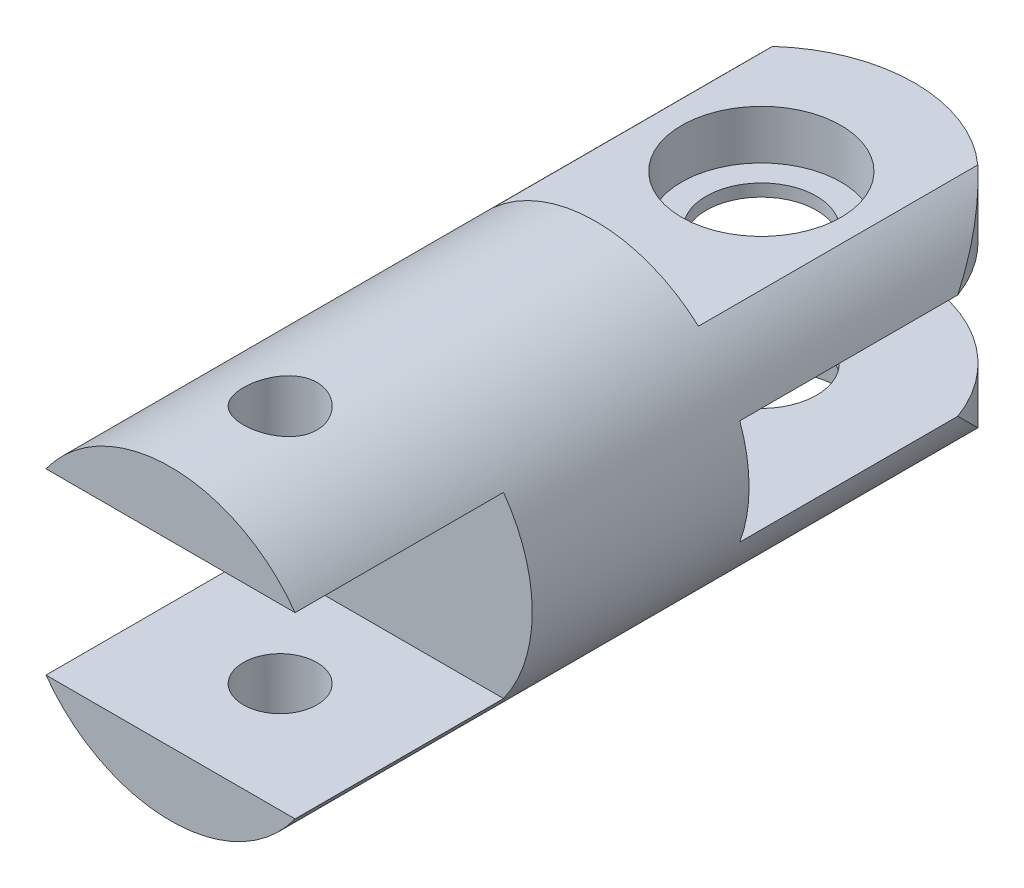
SolidWorks part; units mm, degrees
ref_plane "정면" through (0, 0, 0) normal (0, 0, 1) x (1, 0, 0)
ref_plane "윗면" through (0, 0, 0) normal (0, 1, 0) x (1, 0, 0)
ref_plane "우측면" through (0, 0, 0) normal (1, 0, 0) x (0, 0, -1)
sketch "스케치1" plane through (0, 0, 0) normal (0, 0, 1) x (1, 0, 0)
  circle A0 centre (0, 0) radius 12.5
  dimension "D1" = 25
extrude "보스-돌출1" add sketch "스케치1" against normal blind 60.6869 contours A0
sketch "스케치2" plane through (0, 0, -60.6869) normal (0, 0, -1) x (-1, 0, 0)
  line L0 (18.4039, 0) -> (-28.4221, 0) construction
  line L1 (8.3714, 9.2827) -> (-8.3714, 9.2827)
  line L2 (11.7434, 4.2827) -> (-11.7434, 4.2827)
  line L3 (8.3714, -9.2827) -> (-8.3714, -9.2827)
  line L4 (11.7434, -4.2827) -> (-11.7434, -4.2827)
  arc A0 (-11.7434, 4.2827) -> (-11.7434, -4.2827) centre (0, 0) ccw
  circle A1 centre (0, 0) radius 12.5
  arc A2 (8.3714, 9.2827) -> (-8.3714, 9.2827) centre (0, 0) ccw
  arc A3 (-8.3714, -9.2827) -> (8.3714, -9.2827) centre (0, 0) ccw
  arc A4 (11.7434, -4.2827) -> (11.7434, 4.2827) centre (0, 0) ccw
  point P8 (-11.8869, 3.8668)
  dimension "D3" = 5
  dimension "D1" = 0
extrude "컷-돌출1" cut sketch "스케치2" against normal blind 26
ref_plane "평면4" through (12.5, 0, 0) normal (1, 0, 0) x (0, 0, -1)
ref_plane "평면2" through (0, 0, -30.3435) normal (0, 0, -1) x (-1, 0, 0)
sketch "스케치3" plane through (0, 9.2827, 0) normal (0, 1, 0) x (1, 0, 0)
  line L1 (0, 17.9498) -> (0, -5.5116) construction
  line L2 (8.3714, 34.6869) -> (-8.3714, 34.6869) construction
  line L4 (12.5, 0) -> (12.5, 34.6869) construction
  line L5 (12.5, 0) -> (12.5, 64.839) construction
  line L6 (0, 48.1869) -> (50.0464, 48.1869) construction
  line L7 (-22.5, 48.1869) -> (-12.5, 48.1869)
  line L8 (12.5, 48.1869) -> (22.5, 48.1869)
  circle A0 centre (0, 48.1869) radius 4.5
  arc A1 (12.5, 48.1869) -> (-12.5, 48.1869) centre (0, 48.1869) ccw
  arc A2 (22.5, 48.1869) -> (-22.5, 48.1869) centre (0, 48.1869) ccw
  dimension "D1" = 9
  dimension "D2" = 13.5
  dimension "D3" = 10
extrude "컷-돌출2" cut sketch "스케치3" against normal blind 34.1239
sketch "스케치6" plane through (0, 9.2827, 0) normal (0, 1, 0) x (1, 0, 0)
  circle A0 centre (0, 48.1869) radius 6.5
  dimension "D1" = 13
extrude "컷-돌출5" cut sketch "스케치6" against normal blind 4
ref_plane "평면1" through (0, 0, 0) normal (0, -1, 0) x (-1, 0, 0)
mirror "대칭 복사3" about plane through (0, 0, 0) normal (0, 1, 0) of "컷-돌출5"
sketch "스케치8" plane through (0, 0, 0) normal (0, 0, 1) x (1, 0, 0)
  line L0 (10.1592, 7.2829) -> (-10.1592, 7.2829)
  line L2 (13.75, 0) -> (-13.75, 0) construction
  line L4 (10.1592, -7.2829) -> (-10.1592, -7.2829)
  arc A0 (10.1592, -7.2829) -> (10.1592, 7.2829) centre (0, 0) ccw
  circle A1 centre (0, 0) radius 12.5
  arc A2 (-10.1592, 7.2829) -> (-10.1592, -7.2829) centre (0, 0) ccw
  circle A5 centre (0, 0) radius 12.5 construction
  point P5 (0, 0)
  point P6 (9.168, -8.1775)
  point P9 (-11.2237, -5.4615)
  point P12 (12.4989, 0)
  point P13 (11.2437, -5.4615)
  point P16 (-12.5, 0)
  point P17 (0, 0)
  point P18 (-9.5005, -8.1235)
  dimension "D1" = 0
extrude "컷-돌출6" cut sketch "스케치8" against normal blind 17 contours L4 A2 L0 A0
sketch "스케치9" plane through (0, -7.2829, 0) normal (0, 1, 0) x (1, 0, 0)
  line L0 (10.1592, 17) -> (-10.1592, 17) construction
  line L1 (0, -4.8583) -> (0, -1.5359) construction
  line L2 (12.5, 17) -> (12.5, 34.6869) construction
  line L3 (12.5, -4.0244) -> (12.5, 34.6869) construction
  line L4 (26.3861, 8.9405) -> (-34.052, 8.9405) construction
  circle A0 centre (0, 8.9405) radius 3
  arc A1 (-12.5, 8.9405) -> (12.5, 8.9405) centre (0, 8.9405) ccw construction
  dimension "D1" = 6
  dimension "D2" = 8.0595
extrude "컷-돌출7" cut sketch "스케치9" against normal blind 17 and the other way blind 29
